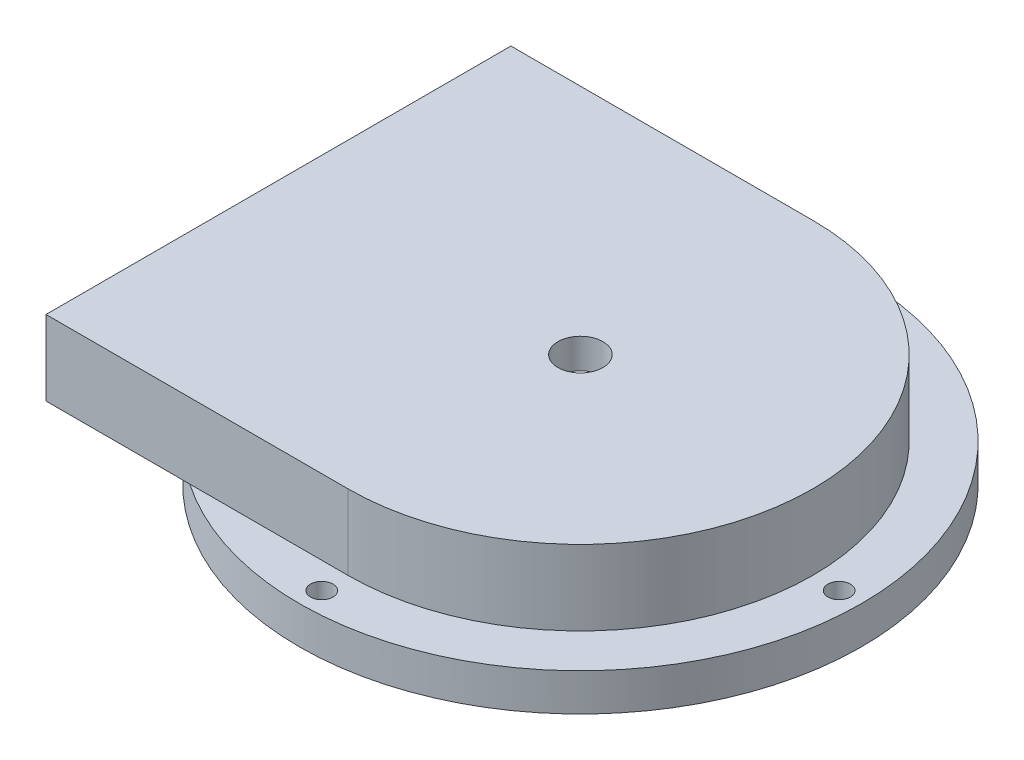
SolidWorks part; units mm, degrees
material "ABS"
ref_plane "Front Plane" through (0, 0, 0) normal (0, 0, 1) x (1, 0, 0)
ref_plane "Top Plane" through (0, 0, 0) normal (0, 1, 0) x (1, 0, 0)
ref_plane "Right Plane" through (0, 0, 0) normal (1, 0, 0) x (0, 0, -1)
sketch "Sketch1" plane through (0, 0, 0) normal (0, 1, 0) x (1, 0, 0)
  circle A0 centre (0, 0) radius 37.5
  circle A1 centre (0, 0) radius 27.5
  dimension "D1" = 75
  dimension "D2" = 55
extrude "Boss-Extrude1" add sketch "Sketch1" along normal blind 5
sketch "Sketch2" plane through (0, 5, 0) normal (0, 1, 0) x (1, 0, 0)
  line L1 (0, 31) -> (-40.2699, 31)
  line L3 (0, -31) -> (-40.2699, -31)
  line L4 (-40.2699, 31) -> (-40.2699, -31)
  arc A0 (0, -31) -> (0, 31) centre (0, 0) ccw
  dimension "D1" = 62
extrude "Boss-Extrude2" add sketch "Sketch2" along normal blind 10
sketch "Sketch3" plane through (0, 5, 0) normal (0, -1, 0) x (1, 0, 0)
  circle A1 centre (0, 0) radius 27.5
  circle A2 centre (0, 0) radius 27.5
  dimension "D1" = 0
extrude "Cut-Extrude2" cut sketch "Sketch3" against normal offset from surface (6 mm away) 4 up to face at (-12.3849, 15, 0)
sketch "Sketch4" plane through (0, 15, 0) normal (0, 1, 0) x (1, 0, 0)
  circle A0 centre (0, 0) radius 3
  dimension "D1" = 6
extrude "Cut-Extrude3" cut sketch "Sketch4" against normal through all both and the other way through all
sketch "Sketch5" plane through (0, 5, 0) normal (0, 1, 0) x (1, 0, 0)
  circle A0 centre (0, 0) radius 34.5 construction
  circle A1 centre (34.5, 0) radius 1.5
  circle A2 centre (0, -34.5) radius 1.5
  circle A3 centre (-34.5, 0) radius 1.5
  circle A4 centre (0, 34.5) radius 1.5
  point P14 (0, 0)
  dimension "D1" = 69
  dimension "D2" = 3
  dimension "D3" = 4
extrude "Cut-Extrude4" cut sketch "Sketch5" against normal through all
